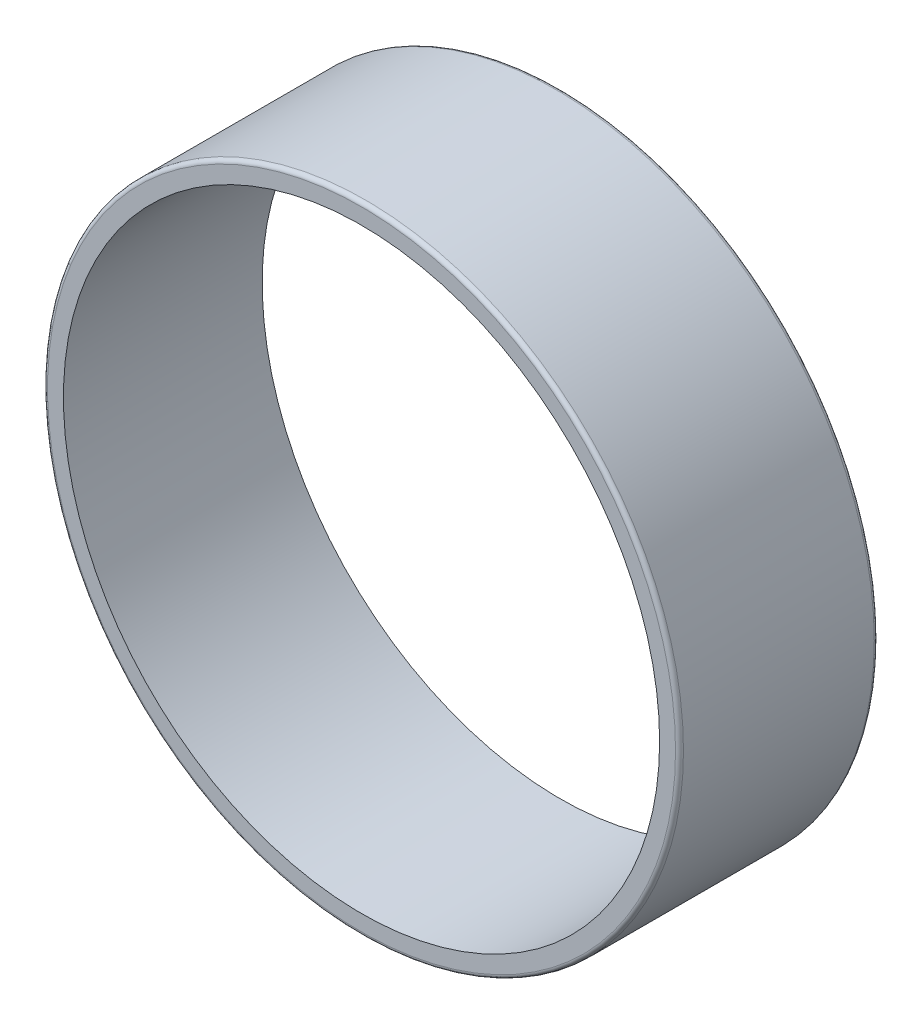
SolidWorks part; units mm, degrees
ref_plane "Ön Düzlem" through (0, 0, 0) normal (0, 0, 1) x (1, 0, 0)
ref_plane "Üst Düzlem" through (0, 0, 0) normal (0, 1, 0) x (1, 0, 0)
ref_plane "Sağ Düzlem" through (0, 0, 0) normal (1, 0, 0) x (0, 0, -1)
sketch "Çizim1" plane through (0, 0, 0) normal (0, 0, 1) x (1, 0, 0)
  circle A0 centre (0, 0) radius 8
  circle A1 centre (0, 0) radius 7.5
  dimension "D1" = 16
  dimension "D2" = 15
extrude "Yükseklik-Ekstrüzyon2" add sketch "Çizim1" along normal blind 5
fillet "Radyus2" radius 0.1 2 edges at (8, 0, 0) (8, 0, 5)
